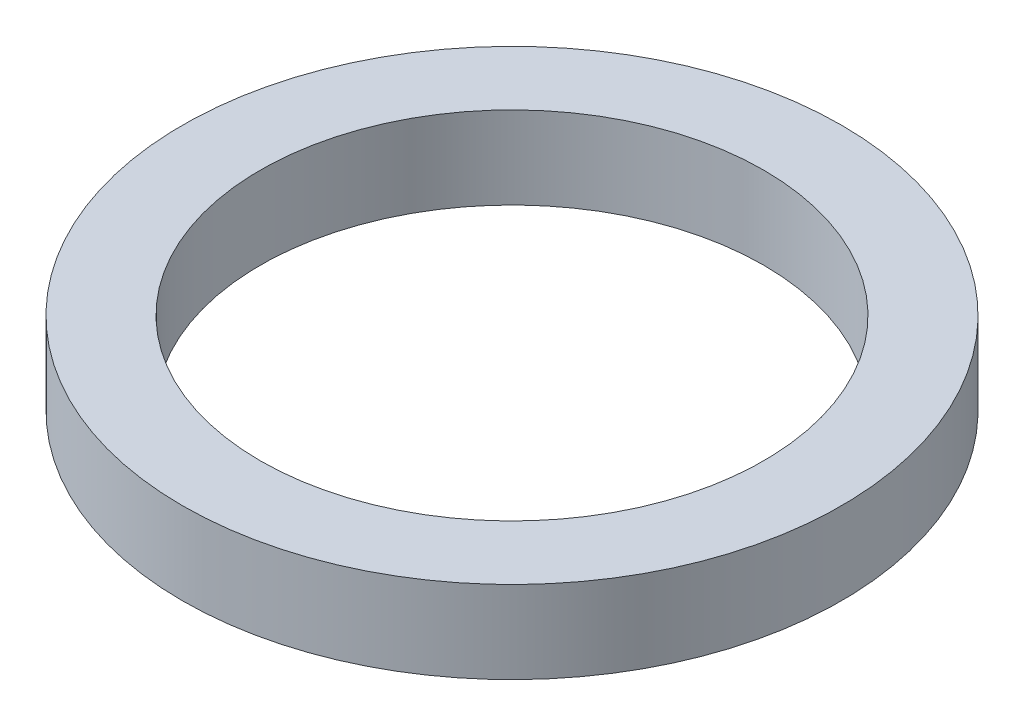
SolidWorks part; units mm, degrees
ref_plane "Front Plane" through (0, 0, 0) normal (0, 0, 1) x (1, 0, 0)
ref_plane "Top Plane" through (0, 0, 0) normal (0, 1, 0) x (1, 0, 0)
ref_plane "Right Plane" through (0, 0, 0) normal (1, 0, 0) x (0, 0, -1)
sketch "Sketch1" plane through (0, 0, 0) normal (0, 1, 0) x (1, 0, 0)
  circle A0 centre (0, 0) radius 27.5
  circle A1 centre (0, 0) radius 36
  dimension "D1" = 55
  dimension "D2" = 72
extrude "Boss-Extrude1" add sketch "Sketch1" along normal mid plane 9
equation "\"Nr\"= 155"
equation "\"module\"= 0.5"
equation "\"pressure_angle\"= 20.0deg"
equation "\"h_a\"= 0.5"
equation "\"h_f\"= 0.625"
equation "\"clr_tip_root\"= 0.125"
equation "\"dp_r\"= 77.5"
equation "\"db_r\"= 72.8261781109079"
equation "\"fw_r\"= 22.13479809822934"
equation "\"alpha_r\"= 0.8539582918412449"
equation "\"beta_r\"= 2.869206906263135"
equation "\"bearing_ID\"= 55"
equation "\"bearing_OD\"= 72"
equation "\"bearing_height\"= 9"
equation "\"clearance_planet\"= 1.5"
equation "\"case_dist\"= 6.5"
equation "\"Motor_case_OD_max\"= 112.3"
equation "\"case_mounting_PCD\"= 104.8"
equation "\"bearing mount thickness\"= 8"
equation "\"case_mounting_hole_dia\"= 3"
equation "\"output_mounting_PCD\"= 80"
equation "\"output_mounting_hole_dia\"= 4"
equation "\"clearance_case_mount_holes_shell_thickness\"= 1"
equation "\"motor_case_OD_base\"= 102.8"
equation "\"sec_carrier_thickness\"= 5"
equation "\"sun_coupler_hub_thickness\"= 4"
equation "\"clearance_sun_coupler_sec_carrier\"= 1.5"
equation "\"clearance_motor_and_case\"= 5"
equation "\"motor_OD\"= 87.8"
equation "\"Motor_case_thickness\"= 2.5"
equation "\"Motor_case_ID\"= 97.8"
equation "\"case_mounting_hole_shift\"= 1.0"
equation "\"output_mounting_nut_wrench_size\"= 7"
equation "\"output_mounting_nut_thickness\"= 3.2"
equation "\"case_mounting_hole_allen_socket_dia\"= 5.5"
equation "\"output_mounting_nut_depth\"= 3"
equation "\"case_mounting_bolt_depth\"= 4.5"
equation "\"Ns\"= 25"
equation "\"Np\"= 65"
equation "\"ring_radial_thickness\"= 5.0"
equation "\"ring_OD\"= 87.5"
equation "\"ring_to_chamfer_clearance\"= 2"
equation "\"Motor_case_OD_base_to_chamfer\"= 5"
equation "\"pattern_offset_from_motor_case_OD_base\"= 3"
equation "\"pattern_bulge_dia\"= 3"
equation "\"pattern_num_bulge\"= 18"
equation "\"pattern_depth\"= 2"
equation "\"motor_height\"= 31.5"
equation "\"case_mounting_wrench_size\"= 5.5"
equation "\"case_mounting_nut_clearance\"= 2"
equation "\"base_plate_thickness\"= 4"
equation "\"case_mounting_nut_thickness\"= 2.4"
equation "\"case_mounting_surface_height\"= 4"
equation "\"motor_mount_hole_PCD\"= 36"
equation "\"motor_mount_hole_dia\"= 4"
equation "\"motor_mount_hole_num\"= 4"
equation "\"central_hole_offset_from_motor_mount_PCD\"= 5"
equation "\"wire_slot_dist_from_center\"= 40"
equation "\"wire_slot_length\"= 10"
equation "\"wire_slot_radius\"= 2.5"
equation "\"driver_upper_holes_dist_from_center\"= 29"
equation "\"driver_lower_holes_dist_from_center\"= 13"
equation "\"driver_side_holes_dist_from_center\"= 22.5"
equation "\"driver_mount_holes_dia\"= 3"
equation "\"driver_mount_inserts_OD\"= 4.8"
equation "\"driver_mount_thickness\"= 1.5"
equation "\"driver_mount_height\"= 6"
equation "\"air_flow_hole_offset\"= 3"
equation "\"num_planet\"= 3"
equation "\"planet_pin_bolt_dia\"= 5"
equation "\"planet_pin_socket_head_dia\"= 8.5"
equation "\"carrier_PCD\"= 45.0"
equation "\"planet_shaft_dia\"= 8"
equation "\"fw_p\"= 22.13479809822934"
equation "\"planet_shaft_step_offset\"= 1"
equation "\"carrier_trapezoidal_support_sun_offset\"= 5"
equation "\"carrier_trapezoidal_support_hole_PCD_offset_bearing_ID\"= 4"
equation "\"carrier_trapezoidal_support_hole_dia\"= 3"
equation "\"carrier_trapezoidal_support_hole_socket_head_dia\"= 5.5"
equation "\"carrier_bearing_step_width\"= 1.5"
equation "\"standard_clearance_1_5mm\"= 1.5"
equation "\"standard_fillet_1_5mm\"= 1.5"
equation "\"sun_shaft_bearing_OD\"= 16"
equation "\"sun_shaft_bearing_width\"= 5"
equation "\"standard_bearing_insertion_chamfer\"= 0.5"
equation "\"D1@Sketch1\"=\"bearing_ID\""
equation "\"D2@Sketch1\"=\"bearing_OD\""
equation "\"D1@Boss-Extrude1\"=\"bearing_height\""
equation "\"D7@Sketch2\"=\"carrier_trapezoidal_support_hole_dia\""
equation "\"D5@Sketch2\"= 360 / ( 4 * \"Ns\" ) - \"alpha_s\""
equation "\"D3@Sketch2\"=\"dp_s\"- 2*\"h_b\""
equation "\"D9@Sketch2\"=\"carrier_trapezoidal_support_sun_offset\""
equation "\"carrier_trapezoidal_support_hole_wrench_size\"= 5.5"
equation "\"planet_pin_bolt_wrench_size\"= 8"
equation "\"pressure angle\"= 20.0deg"
equation "\"motor_output_hole_PCD\"= 23"
equation "\"motor_output_hole_dia\"= 4"
equation "\"motor_output_hole_num\"= 4"
equation "\"h_b\"= 0.625"
equation "\"dp_s\"= 12.5"
equation "\"db_s\"= 11.746157759823856"
equation "\"fw_s_calc\"= 22.13479809822934"
equation "\"alpha_s\"= 0.8539582918412449"
equation "\"beta_s\"= 5.49208341631751"
equation "\"dp_p\"= 32.5"
equation "\"db_p\"= 30.540010175542022"
equation "\"alpha_p\"= 0.8539582918412485"
equation "\"beta_p\"= 1.0613141855482722"
equation "\"planet_bearing_OD\"= 12"
equation "\"planet_bearing_width\"= 3.5"
equation "\"planet_bore\"= 10"
equation "\"sun_shaft_bearing_ID\"= 8"
equation "\"sun_hub_dia\"= 33.0"
equation "\"sun_central_bolt_dia\"= 5"
equation "\"sun_central_bolt_socket_head_dia\"= 8.5"
equation "\"fw_s_used\"= 30.13479809822934"
equation "\"motor_output_hole_CSK_OD\"= 8"
equation "\"motor_output_hole_CSK_head_height\"= 2.0"
equation "\"bearing_retainer_thickness\"= 2"
